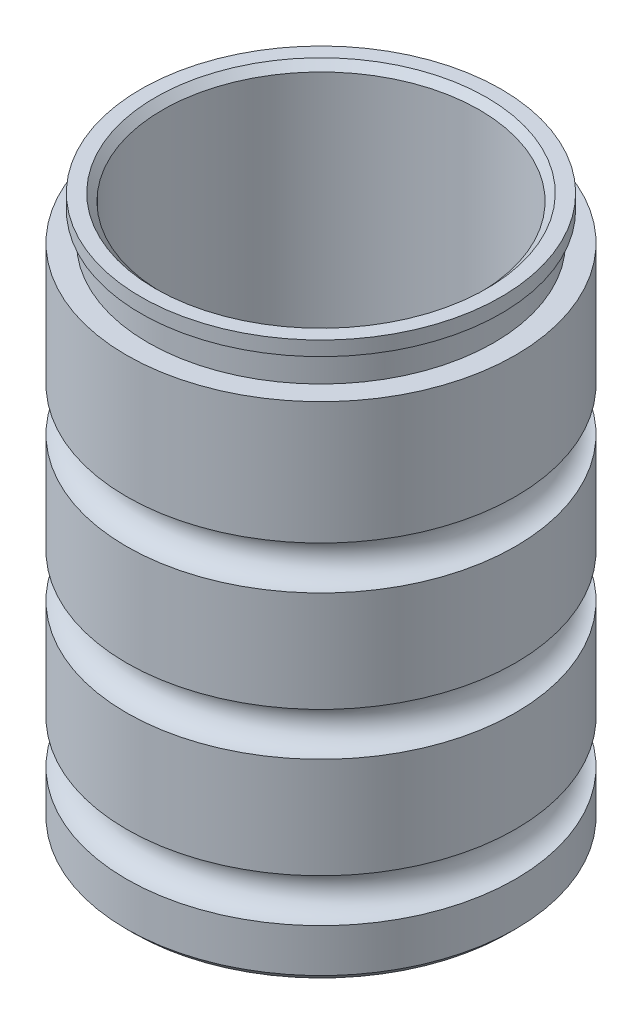
SolidWorks part; units mm, degrees
material "AISI 316 Barre d'acier inoxydable recuit (SS)"
ref_plane "Plan de face" through (0, 0, 0) normal (0, 0, 1) x (1, 0, 0)
ref_plane "Plan de dessus" through (0, 0, 0) normal (0, 1, 0) x (1, 0, 0)
ref_plane "Plan de droite" through (0, 0, 0) normal (1, 0, 0) x (0, 0, -1)
sketch "Esquisse1" plane through (0, 0, 0) normal (0, 0, 1) x (1, 0, 0)
  line L0 (0, -29.1154) -> (0, 30.7029) construction
  line L4 (-2, 24) -> (-2, 3) construction
  line L5 (-2, 3) -> (0, 3) construction
  line L9 (0, 0) -> (-13.5, 0)
  line L10 (-13.5, 0) -> (-13.5, 35) construction
  line L11 (-2, 24) -> (-11, 33) construction
  line L13 (-12.5, 31.7574) -> (-12.5, 38) construction
  line L14 (-12.5, 38) -> (-11, 38)
  line L17 (-11, 38) -> (-11, 33)
  line L18 (-12.5, 38) -> (-12.5, 37)
  line L19 (-12.5, 37) -> (-12, 37)
  line L20 (-12, 37) -> (-12, 35)
  line L29 (-12, 35) -> (-12.5, 35)
  line L33 (-13.5, 35) -> (-12.5, 35)
  line L34 (0, 3) -> (0, 0)
  line L35 (-13.5, 35) -> (-13.5, 26.5)
  line L36 (-13.5, 23.5) -> (-13.5, 16.5)
  line L37 (-13.5, 13.5) -> (-13.5, 6.5)
  line L38 (-13.5, 3.5) -> (-13.5, 0)
  line L39 (-2, 24) -> (-2, 8) construction
  line L40 (-2, 8) -> (0, 12) construction
  line L41 (0, 12) -> (0, 3)
  line L42 (-11, 33) -> (-11, 12)
  line L43 (-11, 12) -> (0, 12)
  arc A0 (-13.5, 26.5) -> (-13.5, 23.5) centre (-13.5, 25) cw
  arc A1 (-13.5, 16.5) -> (-13.5, 13.5) centre (-13.5, 15) cw
  arc A2 (-13.5, 6.5) -> (-13.5, 3.5) centre (-13.5, 5) cw
  point P15 (-11.9368, 36.4)
  point P21 (0, 0)
  dimension "D5" = 1.5
  dimension "D1" = 2
  dimension "D2" = 13.5
  dimension "D3" = 11
  dimension "D4" = 1
  dimension "D6" = 3
  dimension "D7" = 10
  dimension "D8" = 5
  dimension "D9" = 11
  dimension "D10" = 2
  dimension "45" = 45
  dimension "D11" = 5
  dimension "D13" = 21
  dimension "D15" = 0.5
  dimension "D16" = 9
  dimension "D17" = 1
  dimension "38" = 38
revolve "Révolution1" add sketch "Esquisse1" angle 360 about L0
sketch "Esquisse2" plane through (0, 0, 0) normal (0, -1, 0) x (1, 0, 0)
  line L0 (0, 0) -> (13.5, 0) construction
  circle A1 centre (8, 0) radius 2.5
  circle A2 centre (-8, 0) radius 2.5
  circle A5 centre (0, 0) radius 13.5 construction
  point P3 (-7.852, -4.3985)
  point P5 (0, 0)
  point P8 (0, 0)
  point P14 (0, 0)
  dimension "D1" = 5
  dimension "D2" = 8
  dimension "D3" = 2
extrude "Enlèv. mat.-Extru.1" cut sketch "Esquisse2" against normal blind 10
sketch "Esquisse4" plane through (0, 0, 0) normal (0, -1, 0) x (1, 0, 0)
  circle A0 centre (0, 0) radius 2
  dimension "D1" = 4
extrude "Enlèv. mat.-Extru.3" cut sketch "Esquisse4" against normal through all
chamfer "Chanfrein4" distance 0.5 angle 45 2 edges at (0, 12, -2) (0, 0, -2)
chamfer "Chanfrein2" distance 0.5 angle 45 2 edges at (-8, 0, -2.5) (8, 0, -2.5)
chamfer "Chanfrein3" distance 0.5 angle 45 2 edges at (0, 0, -13.5) (0, 38, -11)
equation "\"1à.00mm\"=12"
